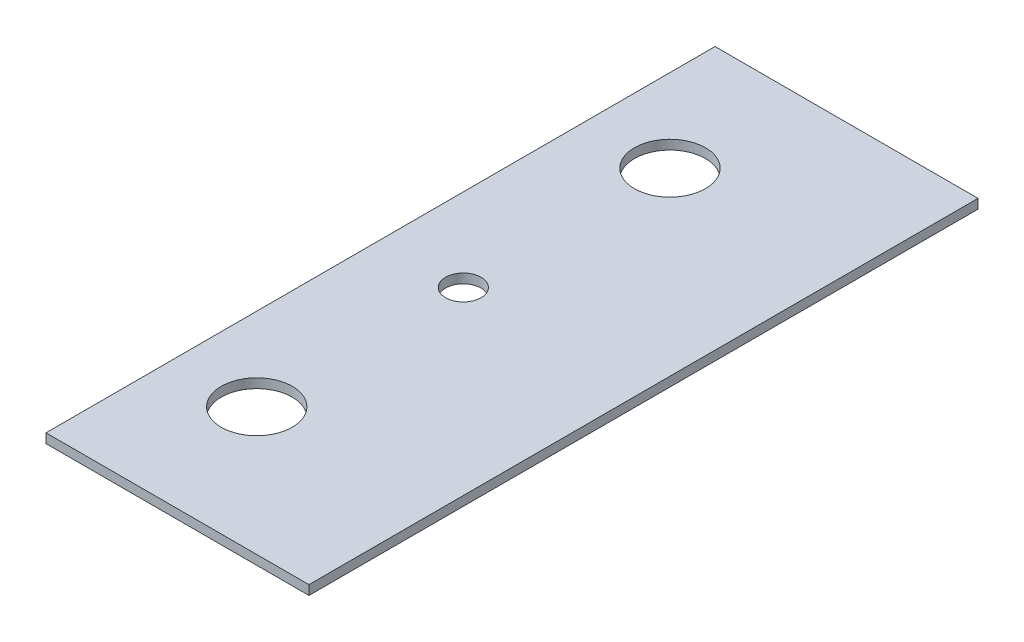
SolidWorks part; units mm, degrees
material "3003-H14"
ref_plane "X-Y Datum" through (0, 0, 0) normal (0, 0, 1) x (1, 0, 0)
ref_plane "X-Z Datum" through (0, 0, 0) normal (0, 1, 0) x (1, 0, 0)
ref_plane "Y-Z Datum" through (0, 0, 0) normal (1, 0, 0) x (0, 0, -1)
sketch "Sketch1" plane through (0, 0, 0) normal (0, 1, 0) x (1, 0, 0)
  line L4 (82.5021, -60.993) -> (82.5021, -117.543)
  line L5 (82.5021, -117.543) -> (104.7271, -117.543)
  line L6 (104.7271, -117.543) -> (104.7271, -60.993)
  line L7 (104.7271, -60.993) -> (82.5021, -60.993)
  line L8 (82.5021, -60.993) -> (82.5021, -117.543)
  line L9 (82.5021, -117.543) -> (104.7271, -117.543)
  line L10 (104.7271, -117.543) -> (104.7271, -60.993)
  line L11 (104.7271, -60.993) -> (82.5021, -60.993)
  circle A0 centre (89.5021, -71.8055) radius 3 construction
  circle A1 centre (89.5021, -89.268) radius 1.5 construction
  circle A2 centre (89.5021, -106.7305) radius 3 construction
  circle A3 centre (89.5021, -89.268) radius 1.5
  circle A4 centre (89.5021, -71.8055) radius 3
  circle A5 centre (89.5021, -106.7305) radius 3
  dimension "D1" = 0
extrude "Boss-Extrude1" add sketch "Sketch1" along normal blind 0.7937
